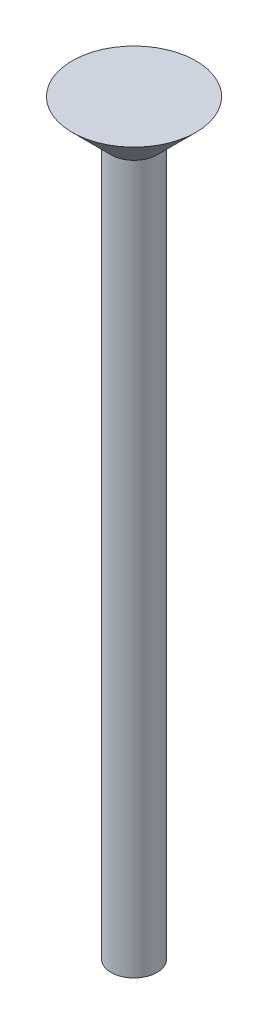
SolidWorks part; units mm, degrees
ref_plane "Front Plane" through (0, 0, 0) normal (0, 0, 1) x (1, 0, 0)
ref_plane "Top Plane" through (0, 0, 0) normal (0, 1, 0) x (1, 0, 0)
ref_plane "Right Plane" through (0, 0, 0) normal (1, 0, 0) x (0, 0, -1)
sketch "Sketch1" plane through (0, 0, 0) normal (0, 0, 1) x (1, 0, 0)
  line L0 (8.3093, 32.7419) -> (8.3093, -18.0581)
  line L1 (8.3093, -18.0581) -> (6.6583, -18.0581)
  line L2 (6.6583, -18.0581) -> (6.6583, 35.5359)
  line L3 (6.6583, 35.5359) -> (11.1033, 35.5359)
  line L4 (11.1033, 35.5359) -> (8.3093, 32.7419)
  dimension "D1" = 50.8
  dimension "D2" = 1.651
  dimension "D3" = 2.794
  dimension "D4" = 135
revolve "Revolve1" add sketch "Sketch1" angle 360 about L2
